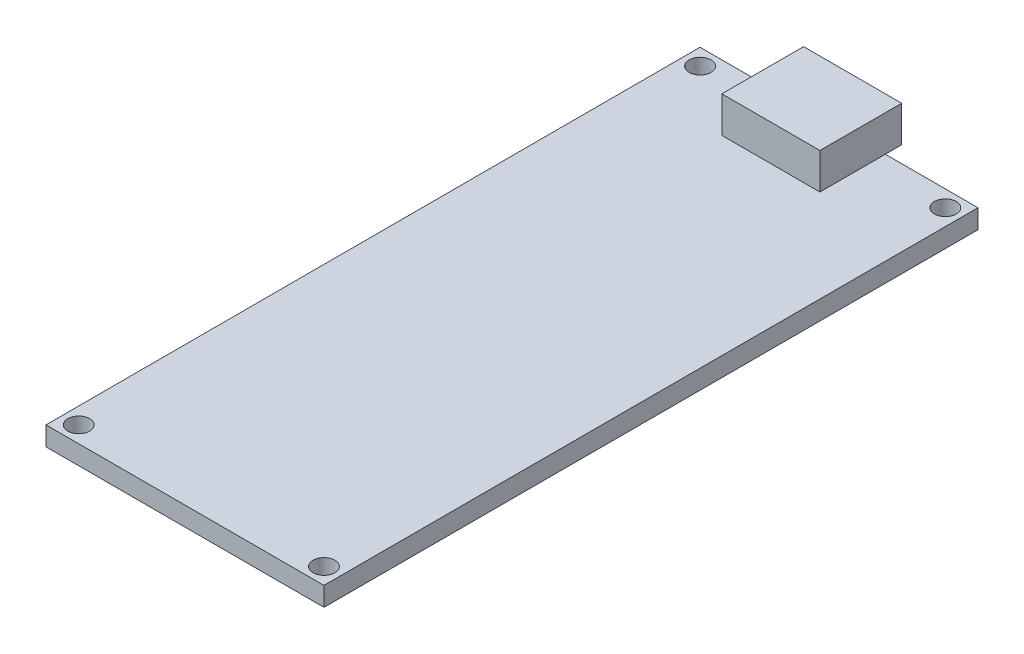
SolidWorks part; units mm, degrees
ref_plane "Front Plane" through (0, 0, 0) normal (0, 0, 1) x (1, 0, 0)
ref_plane "Top Plane" through (0, 0, 0) normal (0, 1, 0) x (1, 0, 0)
ref_plane "Right Plane" through (0, 0, 0) normal (1, 0, 0) x (0, 0, -1)
sketch "Sketch1" plane through (0, 0, 0) normal (0, 1, 0) x (1, 0, 0)
  line L0 (0, 30) -> (0, -30) construction
  line L1 (-12.75, -30) -> (12.75, -30)
  line L2 (-12.75, -30) -> (-12.75, 30)
  line L3 (-12.75, 30) -> (12.75, 30)
  line L4 (12.75, -30) -> (12.75, 30)
  line L5 (-12.75, -30) -> (12.75, 30) construction
  line L6 (-12.75, 30) -> (12.75, -30) construction
  line L7 (-12.75, 0) -> (12.75, 0) construction
  circle A0 centre (11.25, 28.5) radius 1
  circle A1 centre (-11.25, 28.5) radius 1
  circle A2 centre (11.25, -28.5) radius 1
  circle A3 centre (-11.25, -28.5) radius 1
  point P0 (0, 0)
  dimension "D3" = 2
  dimension "D1" = 25.5
  dimension "D2" = 60
  dimension "D4" = 1.5
  dimension "D5" = 1.5
extrude "Boss-Extrude1" add sketch "Sketch1" along normal blind 1.75
sketch "Sketch2" plane through (0, 1.75, 0) normal (0, 1, 0) x (1, 0, 0)
  line L0 (-12.75, 30) -> (-12.75, -30) construction
  line L1 (-4.75, 24) -> (4.25, 24)
  line L2 (-4.75, 24) -> (-4.75, 31.5)
  line L3 (-4.75, 31.5) -> (4.25, 31.5)
  line L4 (4.25, 24) -> (4.25, 31.5)
  line L5 (-4.75, 24) -> (4.25, 31.5) construction
  line L6 (-4.75, 31.5) -> (4.25, 24) construction
  line L8 (12.75, 30) -> (-12.75, 30) construction
  point P0 (-0.25, 27.75)
  dimension "D1" = 9
  dimension "D2" = 7.5
  dimension "D3" = 8
  dimension "D4" = 6
extrude "Boss-Extrude2" add sketch "Sketch2" along normal blind 3.3 contours L3 L4 L1 L2
